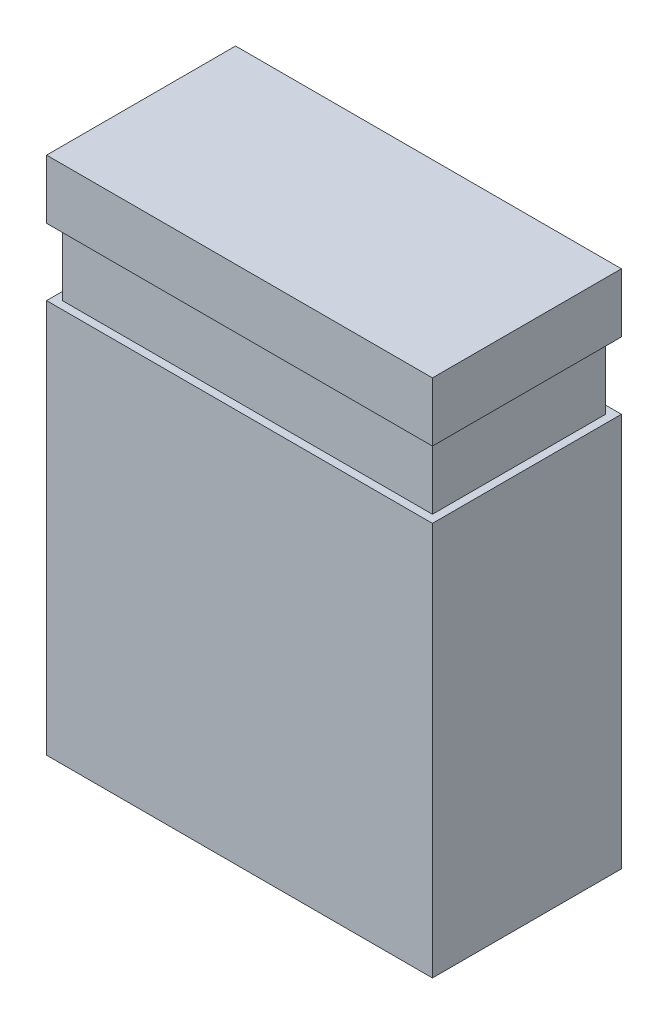
SolidWorks part; units mm, degrees
ref_plane "Přední rovina" through (0, 0, 0) normal (0, 0, 1) x (1, 0, 0)
ref_plane "Horní rovina" through (0, 0, 0) normal (0, 1, 0) x (1, 0, 0)
ref_plane "Pravá rovina" through (0, 0, 0) normal (1, 0, 0) x (0, 0, -1)
sketch "Skica1" plane through (0, 0, 0) normal (0, 0, 1) x (1, 0, 0)
  line L0 (0, 0) -> (-7.5088, 0) construction
  line L2 (0, 0) -> (-4.9, 0)
  line L3 (0, 0) -> (0, 6.6)
  line L4 (0, 6.6) -> (-4.9, 6.6)
  line L5 (-4.9, 0) -> (-4.9, 6.6)
  dimension "D1" = 4.9
  dimension "D2" = 6.6
extrude "Přidat vysunutím1" add sketch "Skica1" along normal blind 2.4
sketch "Skica2" plane through (0, 0, 2.4) normal (0, 0, 1) x (1, 0, 0)
  line L0 (-4.9, 6.6) -> (-4.9, 0) construction
  line L1 (-4.9, 5) -> (0, 5)
  line L2 (-4.9, 5) -> (-4.9, 5.85)
  line L3 (-4.9, 5.85) -> (0, 5.85)
  line L4 (0, 5) -> (0, 5.85)
  line L5 (0, 0) -> (0, 6.6) construction
  line L6 (0, 6.6) -> (-4.9, 6.6) construction
  dimension "D1" = 0.85
  dimension "D2" = 0.75
extrude "Odebrat vysunutím1" cut sketch "Skica2" against normal blind 0.1
sketch "Skica3" plane through (0, 0, 0) normal (1, 0, 0) x (0, 0, -1)
  line L0 (0, 0) -> (0, 6.6) construction
  line L1 (-2.3, 5) -> (0, 5)
  line L2 (-2.3, 5) -> (-2.3, 5.85)
  line L3 (-2.3, 5.85) -> (0, 5.85)
  line L4 (0, 5) -> (0, 5.85)
extrude "Odebrat vysunutím2" cut sketch "Skica3" against normal blind 0.1
sketch "Skica4" plane through (0, 0, 0) normal (0, 0, -1) x (-1, 0, 0)
  line L0 (4.9, 6.6) -> (4.9, 0) construction
  line L1 (0.1, 5) -> (4.9, 5)
  line L2 (0.1, 5) -> (0.1, 5.85)
  line L3 (0.1, 5.85) -> (4.9, 5.85)
  line L4 (4.9, 5) -> (4.9, 5.85)
extrude "Odebrat vysunutím3" cut sketch "Skica4" against normal blind 0.1
sketch "Skica5" plane through (-4.9, 0, 0) normal (-1, 0, 0) x (0, 0, 1)
  line L1 (0.1, 5) -> (2.3, 5)
  line L2 (0.1, 5) -> (0.1, 5.85)
  line L3 (0.1, 5.85) -> (2.3, 5.85)
  line L4 (2.3, 5) -> (2.3, 5.85)
extrude "Odebrat vysunutím4" cut sketch "Skica5" against normal blind 0.1
